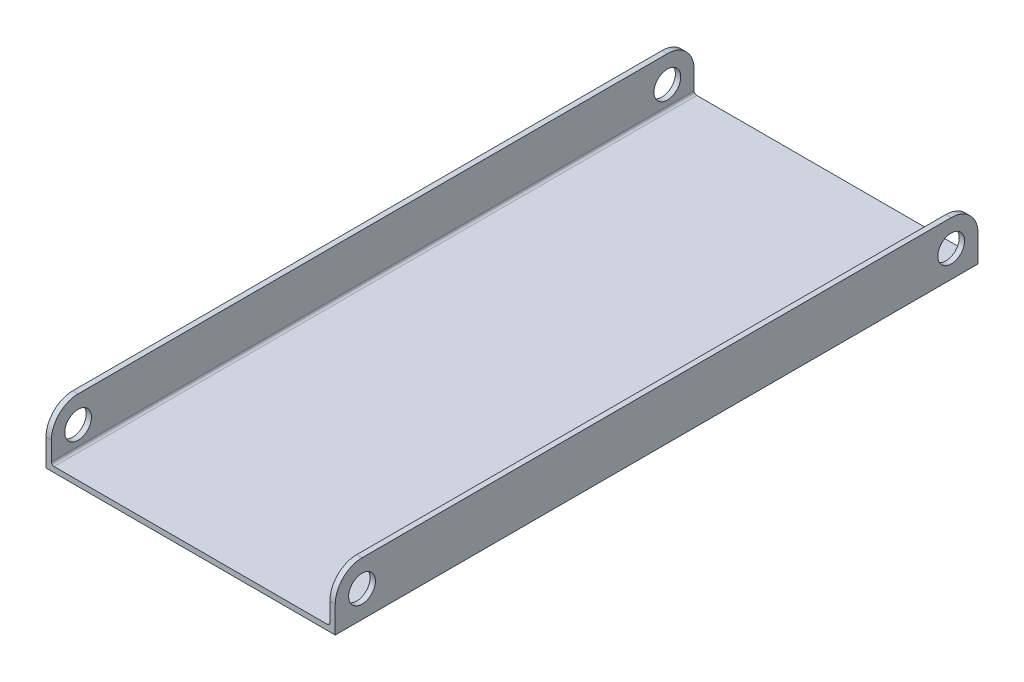
SolidWorks part; units mm, degrees
material "AISI 1020"
ref_plane "Front Plane" through (0, 0, 0) normal (0, 0, 1) x (1, 0, 0)
ref_plane "Top Plane" through (0, 0, 0) normal (0, 1, 0) x (1, 0, 0)
ref_plane "Right Plane" through (0, 0, 0) normal (1, 0, 0) x (0, 0, -1)
sketch "Sketch1" plane through (0, 0, 0) normal (0, 1, 0) x (1, 0, 0)
  line L1 (0, 0) -> (68.58, 0)
  line L2 (0, 0) -> (0, 152.4)
  line L3 (0, 152.4) -> (68.58, 152.4)
  line L4 (68.58, 0) -> (68.58, 152.4)
  dimension "D1" = 68.58
  dimension "D2" = 152.4
extrude "Boss-Extrude1" add sketch "Sketch1" along normal blind 12.7
sketch "Sketch2" plane through (0, 0, 0) normal (0, 0, 1) x (1, 0, 0)
  line L0 (34.29, 12.7) -> (34.29, 0) construction
  line L1 (0, 12.7) -> (68.58, 12.7) construction
  line L2 (0, 0) -> (68.58, 0) construction
  line L4 (1.27, 12.7) -> (67.31, 12.7)
  line L5 (1.27, 12.7) -> (1.27, 1.27)
  line L6 (1.27, 1.27) -> (67.31, 1.27)
  line L7 (67.31, 12.7) -> (67.31, 1.27)
  point P10 (34.29, 1.27)
  dimension "D1" = 66.04
  dimension "D2" = 11.43
extrude "Cut-Extrude1" cut sketch "Sketch2" against normal through all
fillet "Fillet1" radius 0.635 2 edges at (67.31, 1.27, -76.2) (1.27, 1.27, -76.2)
fillet "Fillet2" radius 6.35 4 edges at (67.945, 12.7, -152.4) (67.945, 12.7, 0) (0.635, 12.7, -152.4) (0.635, 12.7, 0)
sketch "Sketch3" plane through (68.58, 0, 0) normal (1, 0, 0) x (0, 0, -1)
  line L0 (0, 6.35) -> (0, 0) construction
  line L1 (0, 0) -> (152.4, 0) construction
  line L2 (152.4, 6.35) -> (152.4, 0) construction
  circle A0 centre (6.35, 6.35) radius 3.175
  circle A1 centre (146.05, 6.35) radius 3.175
  dimension "D1" = 6.35
  dimension "D2" = 6.35
  dimension "D3" = 6.35
  dimension "D4" = 6.35
extrude "Cut-Extrude2" cut sketch "Sketch3" against normal through all
